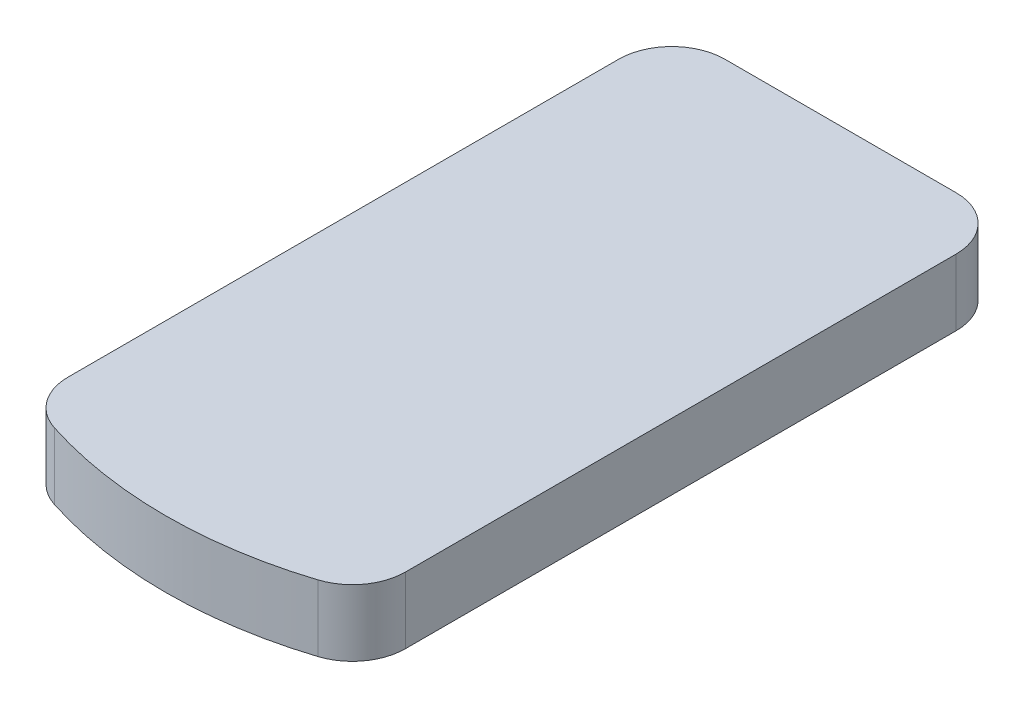
SolidWorks part; units mm, degrees
ref_plane "Alzado" through (0, 0, 0) normal (0, 0, 1) x (1, 0, 0)
ref_plane "Planta" through (0, 0, 0) normal (0, 1, 0) x (1, 0, 0)
ref_plane "Vista lateral" through (0, 0, 0) normal (1, 0, 0) x (0, 0, -1)
sketch "Croquis1" plane through (0, 0, 0) normal (0, 0, 1) x (1, 0, 0)
  line L1 (-31.75, -6.25) -> (31.75, -6.25)
  line L2 (-31.75, -6.25) -> (-31.75, 6.25)
  line L3 (-31.75, 6.25) -> (31.75, 6.25)
  line L4 (31.75, -6.25) -> (31.75, 6.25)
  line L5 (-31.75, -6.25) -> (31.75, 6.25) construction
  line L6 (-31.75, 6.25) -> (31.75, -6.25) construction
  point P0 (0, 0)
  dimension "D1" = 63.5
  dimension "D2" = 12.5
extrude "Saliente-Extruir1" add sketch "Croquis1" along normal blind 127
sketch "Croquis2" plane through (0, 6.25, 0) normal (0, 1, 0) x (1, 0, 0)
  line L0 (-31.75, -127) -> (-31.75, 0) construction
  line L1 (31.75, -127) -> (31.75, 0) construction
  line L2 (31.75, -127) -> (-31.75, -127) construction
  line L3 (-31.75, -120.5393) -> (-31.75, -127)
  line L4 (-31.75, -127) -> (31.75, -127)
  line L5 (31.75, -127) -> (31.75, -120.5393)
  arc A0 (-31.75, -120.5393) -> (31.75, -120.5393) centre (0, -45.7547) ccw
  line M2 (-31.75, 0) -> (-31.75, -127)
  line M3 (-31.75, -127) -> (31.75, -127)
  line M4 (31.75, -127) -> (31.75, 0)
extrude "Cortar-Extruir1" cut sketch "Croquis2" against normal blind 127 contours A0 M2 M3 | A0 L4 M4
fillet "Redondeo1" radius 10 4 edges at (-31.75, 0, 120.5393) (31.75, 0, 120.5393) (31.75, 0, 0) (-31.75, 0, 0)
